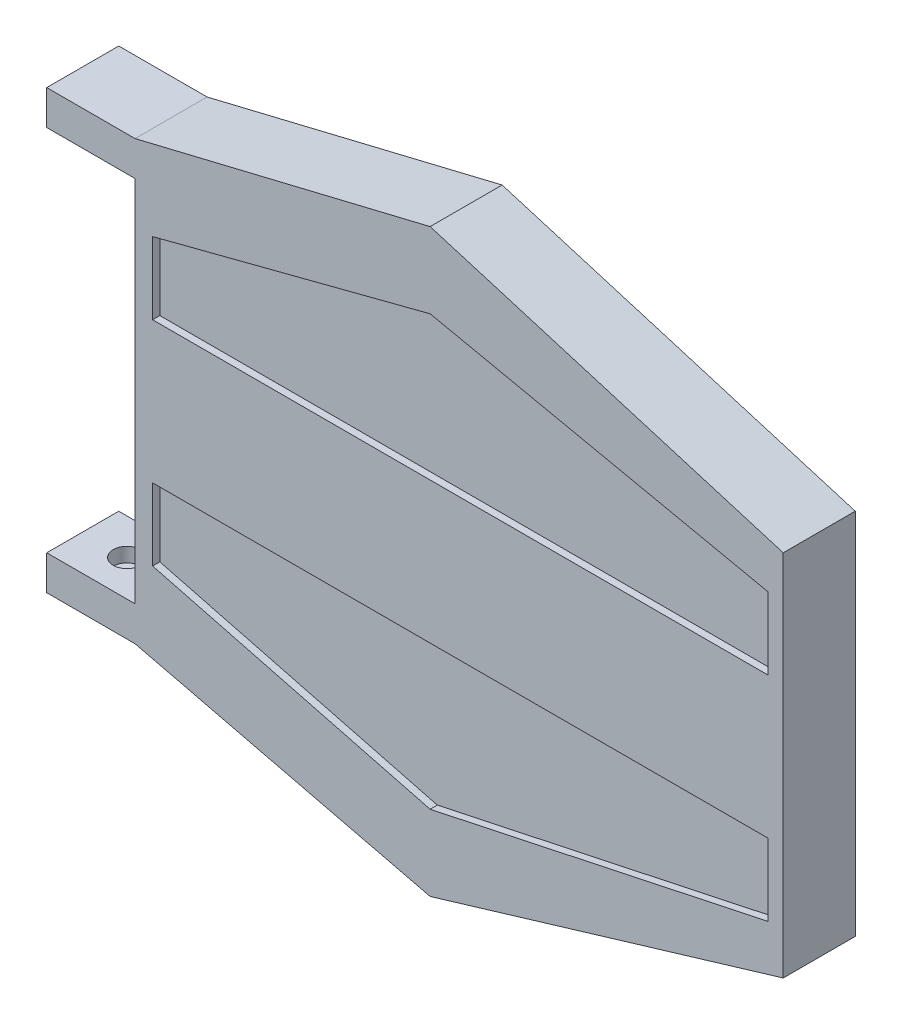
SolidWorks part; units mm, degrees
ref_plane "Front Plane" through (0, 0, 0) normal (0, 0, 1) x (1, 0, 0)
ref_plane "Top Plane" through (0, 0, 0) normal (0, 1, 0) x (1, 0, 0)
ref_plane "Right Plane" through (0, 0, 0) normal (1, 0, 0) x (0, 0, -1)
sketch "Sketch1" plane through (0, 0, 0) normal (0, 0, 1) x (1, 0, 0)
  line L0 (-10.4071, 5.2236) -> (0, 7.7386)
  line L1 (0, 7.7386) -> (12.4529, 4.0027)
  line L2 (-10.4071, 4.0027) -> (-10.4071, -8.9839)
  line L5 (12.4529, -8.9839) -> (12.4529, 4.0027)
  line L6 (-12.275, 5.2236) -> (-10.4071, 5.2236)
  line L7 (-12.275, 5.2236) -> (-13.5203, 5.2236)
  line L8 (-13.5203, 5.2236) -> (-13.5203, 4.0027)
  line L9 (-13.5203, 4.0027) -> (-10.4071, 4.0027)
  line L10 (-12.275, -10.2047) -> (-10.4071, -10.2047)
  line L11 (-12.275, -10.2047) -> (-13.5203, -10.2047)
  line L12 (-13.5203, -10.2047) -> (-13.5203, -8.9839)
  line L13 (-13.5203, -8.9839) -> (-10.4071, -8.9839)
  line L14 (0, -12.7198) -> (12.4529, -8.9839)
  line L15 (-10.4071, -10.2047) -> (0, -12.7198)
  dimension "D1" = 22.86
  dimension "D2" = 12.9866
extrude "Boss-Extrude1" add sketch "Sketch1" along normal blind 2.54
sketch "Sketch4" plane through (0, 0, 2.54) normal (0, 0, 1) x (1, 0, 0)
  line L0 (12.4529, -2.4906) -> (-10.4071, -2.4906) construction
  line L1 (12.4529, -8.9839) -> (12.4529, 4.0027) construction
  line L2 (-10.4071, 4.0027) -> (-10.4071, -8.9839) construction
  line L3 (-9.7862, 0) -> (11.9232, 0)
  line L4 (11.9232, 0) -> (11.9232, 2.54)
  line L5 (11.9232, 2.54) -> (0, 5.0755)
  line L6 (0, 5.0755) -> (-9.7862, 2.54)
  line L7 (-9.7862, 2.54) -> (-9.7862, 0)
  line L8 (0, -10.0567) -> (-9.7862, -7.5212)
  line L9 (11.9232, -7.5212) -> (0, -10.0567)
  line L10 (11.9232, -4.9812) -> (11.9232, -7.5212)
  line L11 (-9.7862, -4.9812) -> (11.9232, -4.9812)
  line L12 (-9.7862, -7.5212) -> (-9.7862, -4.9812)
  dimension "D1" = 2.54
  dimension "D2" = 2.54
extrude "Cut-Extrude2" cut sketch "Sketch4" against normal blind 0.254
sketch "Sketch5" plane through (0, -8.9839, 0) normal (0, 1, 0) x (1, 0, 0)
  circle A0 centre (-11.9637, -1.27) radius 0.482
extrude "Cut-Extrude3" cut sketch "Sketch5" against normal blind 0.508
sketch "Sketch6" plane through (0, 4.0027, 0) normal (0, -1, 0) x (1, 0, 0)
  circle A0 centre (-11.9637, 1.27) radius 0.508
extrude "Cut-Extrude4" cut sketch "Sketch6" against normal blind 0.508
